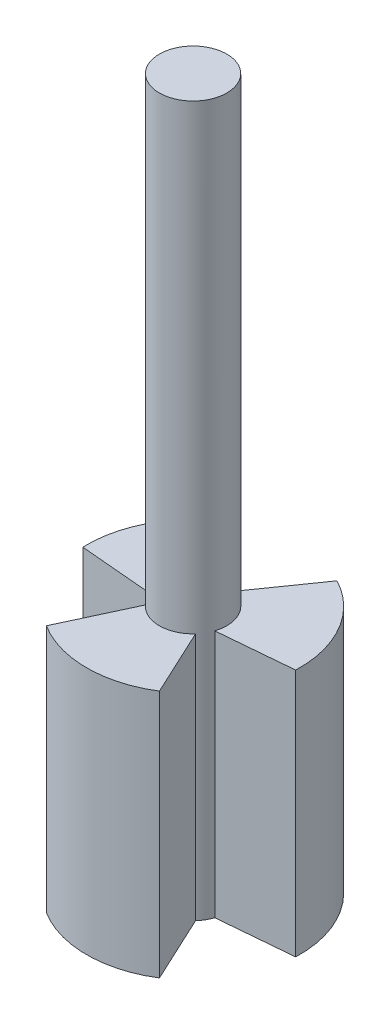
SolidWorks part; units mm, degrees
ref_plane "Front Plane" through (0, 0, 0) normal (0, 0, 1) x (1, 0, 0)
ref_plane "Top Plane" through (0, 0, 0) normal (0, 1, 0) x (1, 0, 0)
ref_plane "Right Plane" through (0, 0, 0) normal (1, 0, 0) x (0, 0, -1)
sketch "Sketch1" plane through (0, 0, 0) normal (0, 1, 0) x (1, 0, 0)
  circle A0 centre (0, 0) radius 241.3
  dimension "D1" = 482.6
extrude "Boss-Extrude1" add sketch "Sketch1" along normal blind 5080
sketch "Sketch2" plane through (0, 0, 0) normal (0, -1, 0) x (1, 0, 0)
  circle A0 centre (0, 0) radius 762
  dimension "D1" = 1524
extrude "Boss-Extrude3" add sketch "Sketch2" against normal blind 1778 contours A0
sketch "Sketch4" plane through (0, 1778, 0) normal (0, 1, 0) x (1, 0, 0)
  line L0 (0, 0) -> (0, 241.3) construction
  line L1 (-50.4256, 235.9724) -> (-356.6893, 673.3623)
  line L2 (50.4256, 235.9724) -> (356.6893, 673.3623)
  arc A0 (-50.4256, 235.9724) -> (50.4256, 235.9724) centre (0, 0) cw
  circle A1 centre (0, 0) radius 241.3 construction
  circle A2 centre (0, 0) radius 241.3 construction
  circle A3 centre (0, 0) radius 762 construction
  dimension "D1" = 101.6
  dimension "D2" = 70
extrude "Cut-Extrude2" cut sketch "Sketch4" against normal blind 1778 and the other way through all flip side to cut
pattern_circular "CirPattern1" count 3 over 360 about axis through (0, 5080, 0) along (0, -1, 0) of "Cut-Extrude2"
scale "Scale1" scale about centroid uniform scaling yes scale factor 0.02
